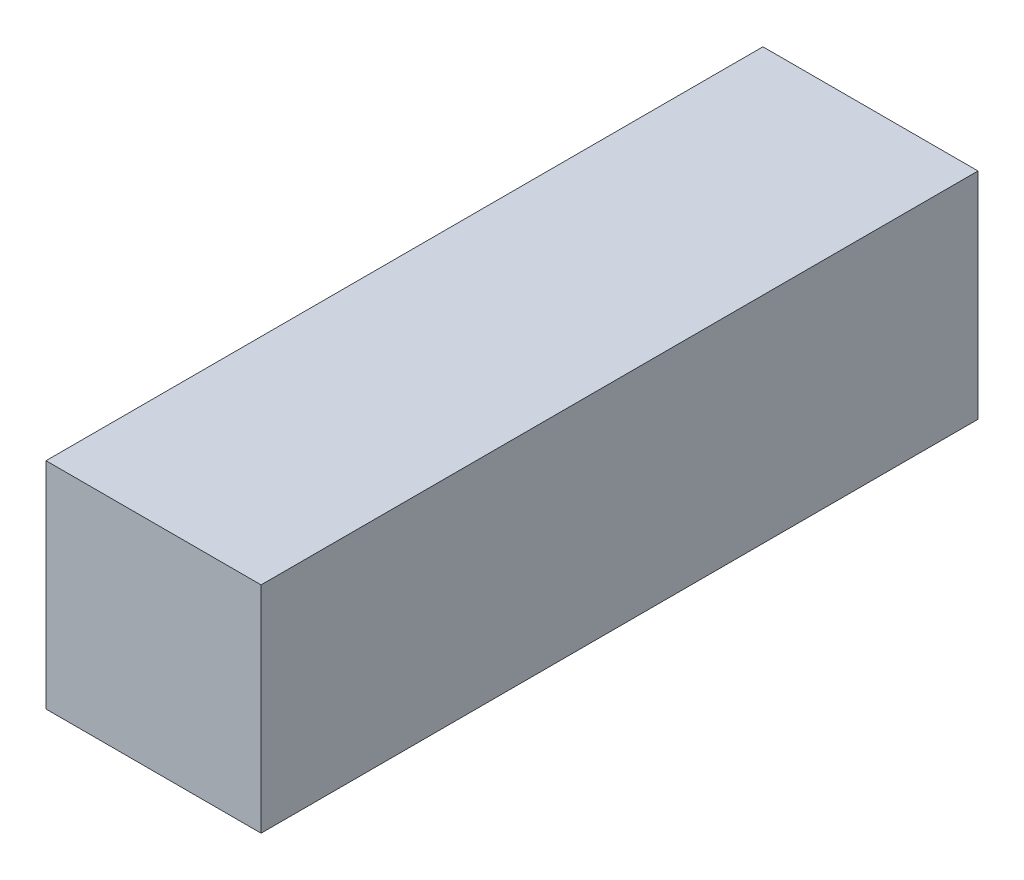
SolidWorks part; units mm, degrees
material "Plain Carbon Steel"
ref_plane "Front Plane" through (0, 0, 0) normal (1, 0, 0) x (0, 1, 0)
ref_plane "Top Plane" through (0, 0, 0) normal (0, 0, 1) x (0, 1, 0)
ref_plane "Right Plane" through (0, 0, 0) normal (0, 1, 0) x (-1, 0, 0)
sketch "Sketch1" plane through (0, 0, 0) normal (0, 0, 1) x (0, 1, 0)
  line L1 (3, 3) -> (-3, 3)
  line L2 (3, 3) -> (3, -3)
  line L3 (3, -3) -> (-3, -3)
  line L4 (-3, 3) -> (-3, -3)
  line L5 (3, 3) -> (-3, -3) construction
  line L6 (3, -3) -> (-3, 3) construction
  point P0 (0, 0)
  dimension "D1" = 6
  dimension "D2" = 6
extrude "Boss-Extrude1" add sketch "Sketch1" along normal blind 20
